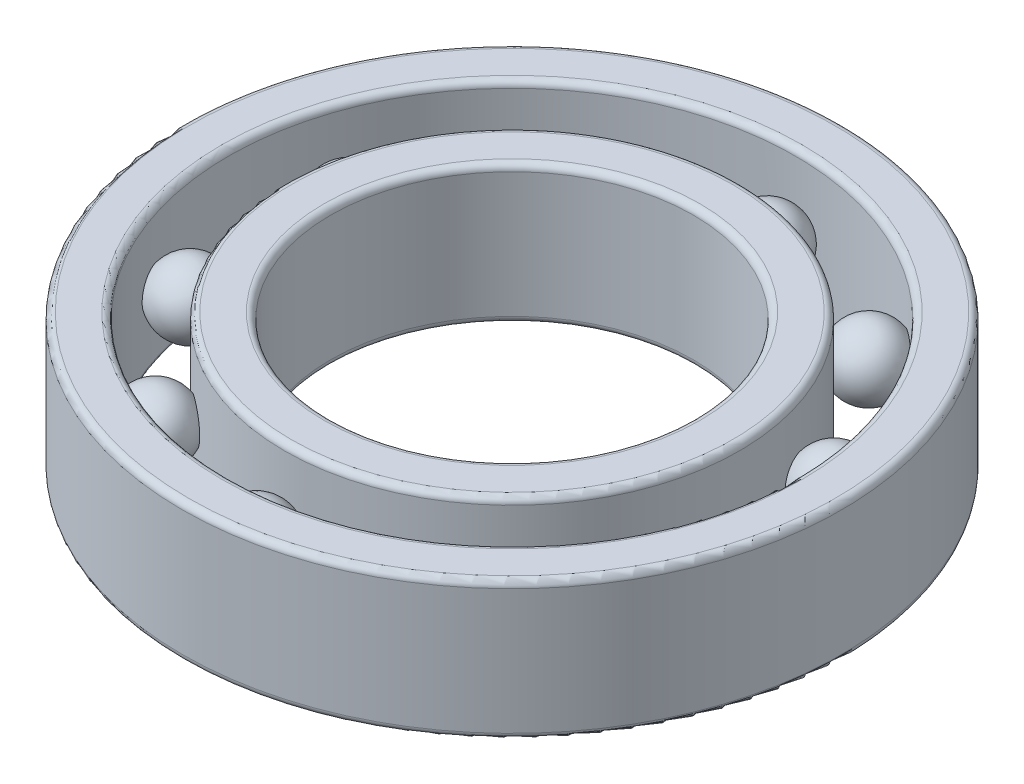
SolidWorks part; units mm, degrees
ref_plane "正面" through (0, 0, 0) normal (0, 0, 1) x (1, 0, 0)
ref_plane "平面" through (0, 0, 0) normal (0, 1, 0) x (1, 0, 0)
ref_plane "右側面" through (0, 0, 0) normal (1, 0, 0) x (0, 0, -1)
sketch "ｽｹｯﾁ1" plane through (0, 0, 0) normal (0, 1, 0) x (1, 0, 0)
  circle A0 centre (0, 0) radius 27.5
  circle A1 centre (0, 0) radius 50
  circle A2 centre (0, 0) radius 34.5
  circle A3 centre (0, 0) radius 43
  dimension "D1" = 55
  dimension "D2" = 100
  dimension "D3" = 7
  dimension "D4" = 7
extrude "ﾎﾞｽ - 押し出し2" add sketch "ｽｹｯﾁ1" along normal mid plane 21 contours A1 A3 | A2 A0
fillet "ﾌｨﾚｯﾄ1" radius 1 4 edges at (0, -10.5, 43) (0, -10.5, 50) (0, 10.5, 43) (0, 10.5, 50)
fillet "ﾌｨﾚｯﾄ2" radius 1 4 edges at (0, -10.5, 34.5) (0, -10.5, 27.5) (0, 10.5, 27.5) (0, 10.5, 34.5)
sketch "ｽｹｯﾁ2" plane through (0, 0, 0) normal (0, 1, 0) x (1, 0, 0)
  line L0 (0, 34.5) -> (0, 43) construction
  line L1 (0, 33.5) -> (0, 44)
  circle A0 centre (0, 0) radius 34.5 construction
  circle A1 centre (0, 0) radius 43 construction
  arc A2 (0, 33.5) -> (0, 44) centre (0, 38.75) ccw
  circle A3 centre (0, 0) radius 44 construction
revolve "回転2" add sketch "ｽｹｯﾁ2" angle 360 about L0
pattern_circular "円形ﾊﾟﾀｰﾝ1" count 10 over 360 about axis through (0, 0, 0) along (0, 1, 0) of "回転2"
